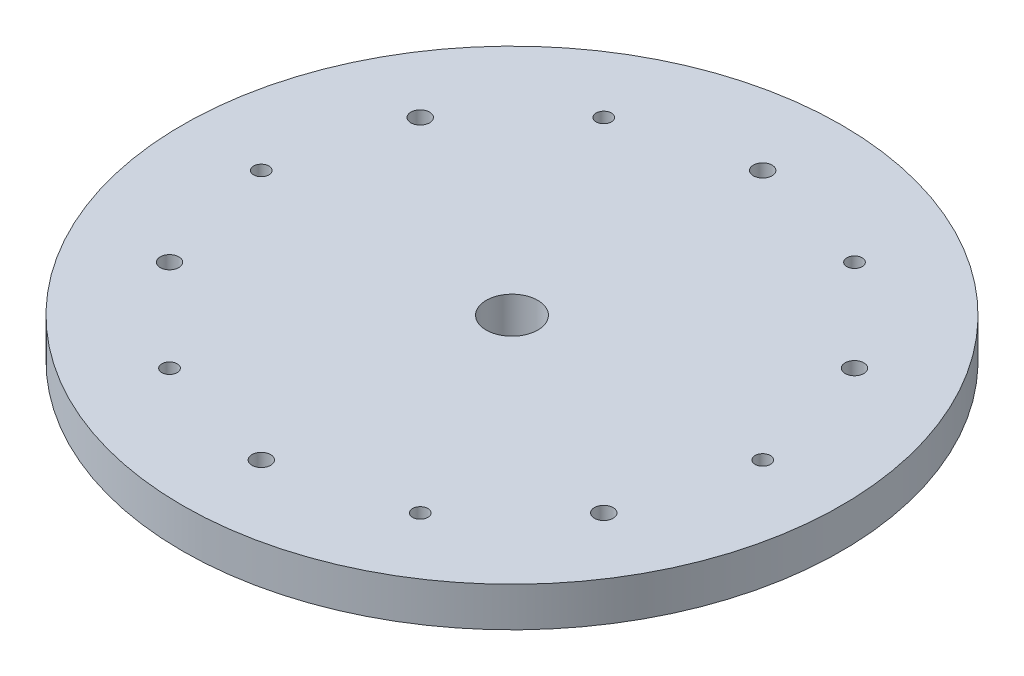
SolidWorks part; units mm, degrees
material "Balsa"
ref_plane "Front" through (0, 0, 0) normal (0, 0, 1) x (1, 0, 0)
ref_plane "Top" through (0, 0, 0) normal (0, 1, 0) x (1, 0, 0)
ref_plane "Right" through (0, 0, 0) normal (1, 0, 0) x (0, 0, -1)
sketch "Sketch1" plane through (0, 0, 0) normal (0, 1, 0) x (1, 0, 0)
  line L0 (0, 0) -> (38.1, 0) construction
  line L1 (19.05, 32.9956) -> (0, 0) construction
  line L2 (0, 0) -> (-19.05, 32.9956) construction
  line L3 (0, 0) -> (0, 38.1) construction
  line L4 (0, 0) -> (-32.9956, 19.05) construction
  line L5 (0, 0) -> (-32.9956, -19.05) construction
  circle A0 centre (0, 0) radius 50
  circle A1 centre (38.1, 0) radius 1.25
  circle A2 centre (19.05, -32.9956) radius 1.25
  circle A3 centre (-19.05, -32.9956) radius 1.25
  circle A4 centre (-38.1, 0) radius 1.25
  circle A5 centre (-19.05, 32.9956) radius 1.25
  circle A6 centre (19.05, 32.9956) radius 1.25
  circle A7 centre (0, 38.1) radius 1.5
  circle A8 centre (32.9956, 19.05) radius 1.5
  circle A9 centre (32.9956, -19.05) radius 1.5
  circle A10 centre (0, -38.1) radius 1.5
  circle A11 centre (-32.9956, -19.05) radius 1.5
  circle A12 centre (-32.9956, 19.05) radius 1.5
  circle A13 centre (0, 0) radius 4
  dimension "D1" = 100
  dimension "D2" = 2.5
  dimension "D5" = 3
  dimension "D7" = 8
  dimension "D3" = 38.1
  dimension "D4" = 6
  dimension "D6" = 6
extrude "Boss-Extrude1" add sketch "Sketch1" along normal blind 6
other "Move Face1" face at (0, 6, 4) face at (0, 6, 50) face at (38.1, 6, 1.25) face at (0, 6, -36.6) face at (19.05, 6, 34.2456) face at (-19.05, 6, 34.2456) face at (-38.1, 6, 1.25) face at (-19.05, 6, -31.7456) face at (19.05, 6, -31.7456) face at (32.9956, 6, -17.55) face at (32.9956, 6, 20.55) face at (0, 6, 39.6) face at (-32.9956, 6, 20.55) face at (-32.9956, 6, -17.55) parameters "D1"=0.08
